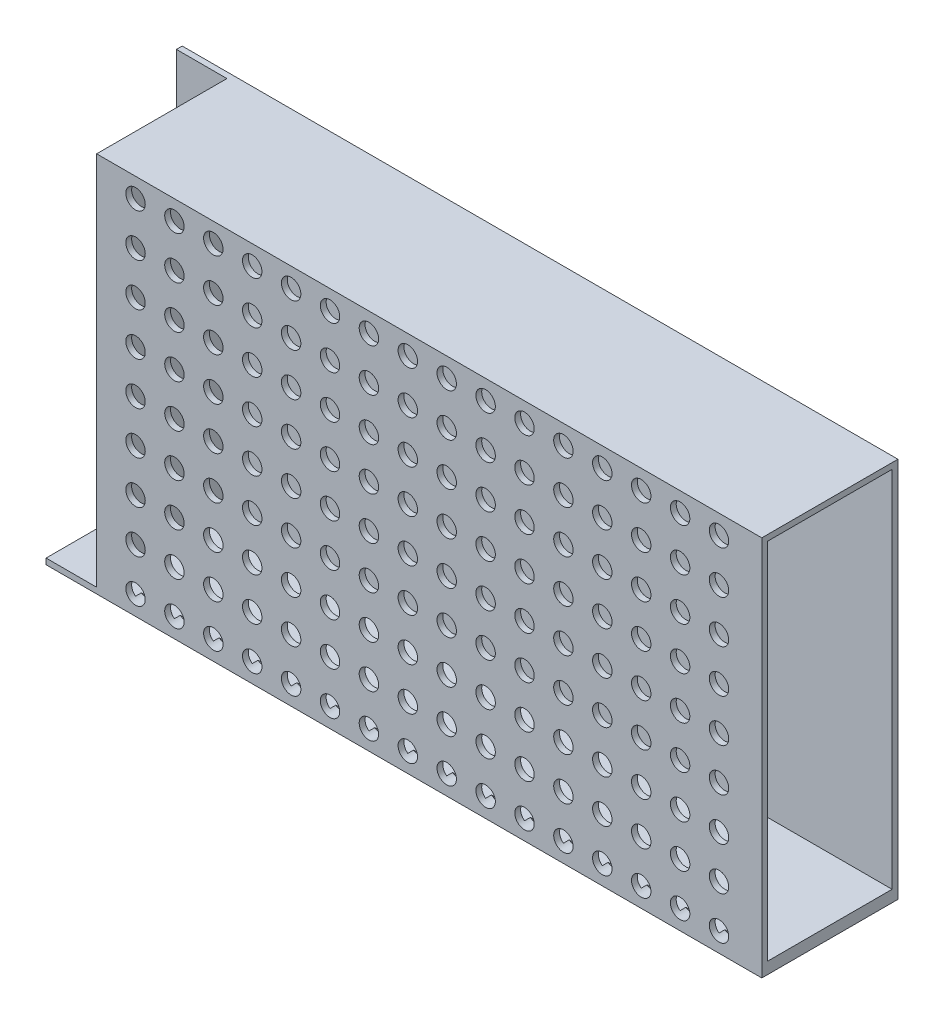
SolidWorks part; units mm, degrees
material "Alloy Steel"
ref_plane "Front Plane" through (0, 0, 0) normal (0, 0, 1) x (1, 0, 0)
ref_plane "Top Plane" through (0, 0, 0) normal (0, 1, 0) x (1, 0, 0)
ref_plane "Right Plane" through (0, 0, 0) normal (1, 0, 0) x (0, 0, -1)
sketch "Sketch1" plane through (0, 0, 0) normal (0, 0, 1) x (1, 0, 0)
  line L1 (92, -49) -> (-92, -49)
  line L2 (92, -49) -> (92, 49)
  line L3 (92, 49) -> (-92, 49)
  line L4 (-92, -49) -> (-92, 49)
  line L5 (92, -49) -> (-92, 49) construction
  line L6 (92, 49) -> (-92, -49) construction
  point P0 (0, 0)
  dimension "D1" = 98
  dimension "D2" = 184
extrude "Boss-Extrude1" add sketch "Sketch1" along normal blind 35
sketch "Sketch2" plane through (0, 0, 35) normal (0, 0, 1) x (1, 0, 0)
  line L0 (-92, 49) -> (-79, 49)
  line L1 (92, 49) -> (-92, 49) construction
  line L2 (-79, 49) -> (-79, -47.5)
  line L3 (-79, -47.5) -> (-92, -47.5)
  line L4 (-92, 49) -> (-92, -49) construction
  line L5 (-92, -47.5) -> (-92, 49)
  line L6 (-92, -49) -> (92, -49) construction
  dimension "D1" = 1.5
  dimension "D2" = 13
extrude "Cut-Extrude1" cut sketch "Sketch2" along direction (0, 0, -1) on the side against the normal offset from surface (33.5 mm away) 1.5
sketch "Sketch3" plane through (92, 0, 0) normal (1, 0, 0) x (0, 0, -1)
  line L0 (-35, -49) -> (-35, 49) construction
  line L1 (-1.5, -46) -> (-33.5, -46)
  line L2 (-1.5, -46) -> (-1.5, 47.5)
  line L3 (-1.5, 47.5) -> (-33.5, 47.5)
  line L4 (-33.5, -46) -> (-33.5, 47.5)
  line L5 (-1.5, -46) -> (-33.5, 47.5) construction
  line L6 (-1.5, 47.5) -> (-33.5, -46) construction
  line L7 (0, -49) -> (0, 49) construction
  line L8 (-35, -49) -> (0, -49) construction
  line L9 (-35, 49) -> (0, 49) construction
  point P0 (-17.5, 0.75)
  dimension "D1" = 1.5
  dimension "D2" = 1.5
  dimension "D3" = 3
  dimension "D4" = 1.5
extrude "Cut-Extrude2" cut sketch "Sketch3" along direction (-1, 0, 0) on the side against the normal offset from surface (169.5 mm away) 1.5
sketch "Sketch4" plane through (0, 0, 35) normal (0, 0, 1) x (1, 0, 0)
  line L0 (92, 49) -> (-79, 49) construction
  line L1 (-79, -47.5) -> (-79, 49) construction
  circle A0 centre (-69, 44) radius 2.5
  circle A1 centre (-69, 33) radius 2.5
  circle A2 centre (-69, 22) radius 2.5
  circle A3 centre (-69, 11) radius 2.5
  circle A4 centre (-69, 0) radius 2.5
  circle A5 centre (-69, -11) radius 2.5
  circle A6 centre (-69, -22) radius 2.5
  circle A7 centre (-69, -33) radius 2.5
  circle A8 centre (-69, -44) radius 2.5
  dimension "D1" = 5
  dimension "D2" = 5
  dimension "D3" = 10
  dimension "D4" = 9
extrude "Cut-Extrude4" cut sketch "Sketch4" against normal blind 3
pattern_linear "LPattern1" count 16 spacing 10 along (1, 0, 0) of "Cut-Extrude4"
